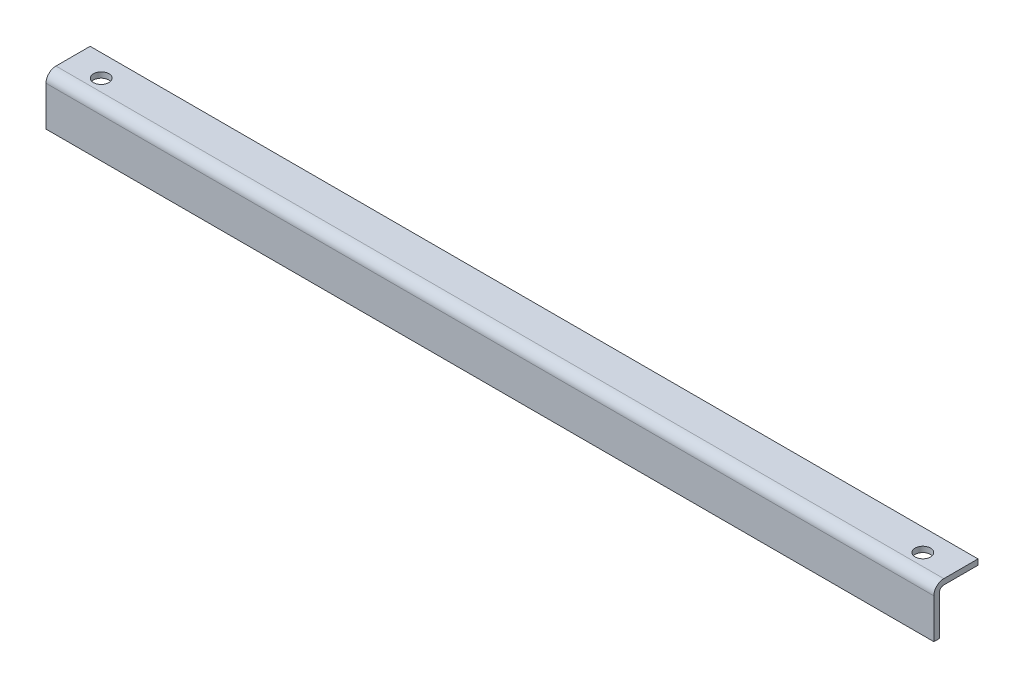
SolidWorks part; units mm, degrees
material "Galvanized Steel"
ref_plane "Front Plane" through (0, 0, 0) normal (0, 0, 1) x (1, 0, 0)
ref_plane "Top Plane" through (0, 0, 0) normal (0, 1, 0) x (1, 0, 0)
ref_plane "Right Plane" through (0, 0, 0) normal (1, 0, 0) x (0, 0, -1)
sketch "Sketch1" plane through (0, 0, 0) normal (0, 1, 0) x (1, 0, 0)
  line L1 (-201.1311, -10) -> (201.1311, -10)
  line L2 (-201.1311, -10) -> (-201.1311, 10)
  line L3 (-201.1311, 10) -> (201.1311, 10)
  line L4 (201.1311, -10) -> (201.1311, 10)
  line L5 (-201.1311, -10) -> (201.1311, 10) construction
  line L6 (-201.1311, 10) -> (201.1311, -10) construction
  point P0 (0, 0)
  dimension "D1" = 402.2622
  dimension "D2" = 20
extrude "Boss-Extrude1" add sketch "Sketch1" along normal blind 2.5
sketch "Sketch2" plane through (0, 2.5, 0) normal (0, 1, 0) x (1, 0, 0)
  line L0 (201.1311, -10) -> (201.1311, 10) construction
  line L1 (-201.1311, 10) -> (-201.1311, -10) construction
  circle A0 centre (186.1311, 0) radius 3.5
  circle A1 centre (-186.1311, 0) radius 3.5
  dimension "D1" = 7
  dimension "D2" = 15
  dimension "D3" = 7
  dimension "D4" = 15
extrude "Cut-Extrude1" cut sketch "Sketch2" against normal blind 2.5
sketch "Sketch3" plane through (0, 0, 0) normal (0, -1, 0) x (1, 0, 0)
  line L0 (-201.1311, -10) -> (-201.1311, 10) construction
  line L1 (201.1311, 10) -> (-201.1311, 10)
  line L2 (201.1311, 10) -> (201.1311, 7.5)
  line L3 (201.1311, 7.5) -> (-201.1311, 7.5)
  line L4 (-201.1311, 10) -> (-201.1311, 7.5)
  dimension "D1" = 2.5
extrude "Boss-Extrude2" add sketch "Sketch3" along normal blind 20
fillet "Fillet1" radius 2 1 edges at (0, 0, 7.5)
fillet "Fillet2" radius 4.5 1 edges at (0, 2.5, 10)
